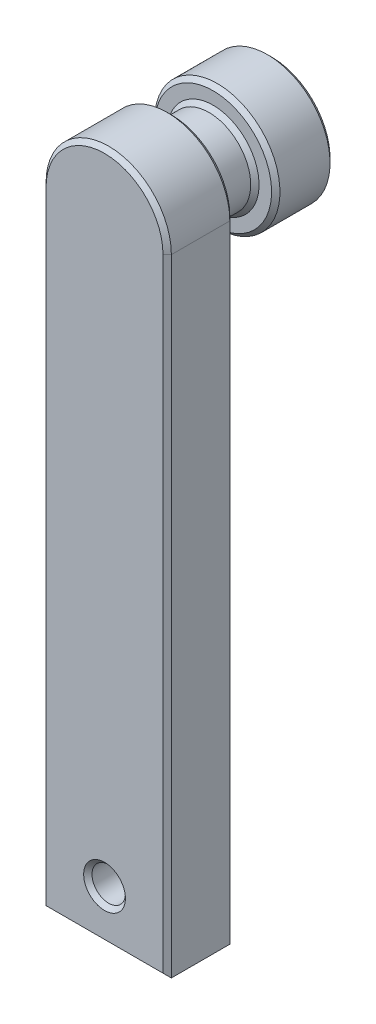
SolidWorks part; units mm, degrees
material "ABS"
ref_plane "Front Plane" through (0, 0, 0) normal (0, 0, 1) x (1, 0, 0)
ref_plane "Top Plane" through (0, 0, 0) normal (0, 1, 0) x (1, 0, 0)
ref_plane "Right Plane" through (0, 0, 0) normal (1, 0, 0) x (0, 0, -1)
sketch "Sketch3" plane through (0, 0, 0) normal (0, 0, 1) x (1, 0, 0)
  line L2 (7.5, 75) -> (7.5, 0)
  line L3 (7.5, 0) -> (-7.5, 0)
  line L4 (-7.5, 75) -> (-7.5, 0)
  line L5 (7.5, 75) -> (-7.5, 0) construction
  line L6 (7.5, 0) -> (-7.5, 75) construction
  arc A0 (-7.5, 75) -> (7.5, 75) centre (0, 75) cw
  circle A1 centre (0, 6) radius 2
  point P0 (0, 37.5)
  point P5 (0, 0)
  point P10 (0, 0)
  dimension "D3" = 6
  dimension "D4" = 4
  dimension "D1" = 75
  dimension "D2" = 15
extrude "Boss-Extrude1" add sketch "Sketch3" along normal blind 8
sketch "Sketch4" plane through (0, 0, 0) normal (0, 0, 1) x (1, 0, 0)
  circle A0 centre (0, 75) radius 5
  arc A1 (7.5, 75) -> (-7.5, 75) centre (0, 75) ccw construction
  dimension "D1" = 10
extrude "Boss-Extrude2" add sketch "Sketch4" against normal blind 5
sketch "Sketch5" plane through (0, 0, -5) normal (0, 0, -1) x (-1, 0, 0)
  circle A0 centre (0, 75) radius 7.5
  circle A1 centre (0, 75) radius 5 construction
  arc A2 (7.5, 75) -> (-7.5, 75) centre (0, 75) ccw construction
  point P2 (0, 0)
extrude "Boss-Extrude3" add sketch "Sketch5" along normal blind 7
chamfer "Chamfer1" distance 0.5 angle 45 13 edges at (0, 82.5, 8) (7.5, 37.5, 8) (0, 0, 8) (-7.5, 37.5, 8) (-7.5, 75, -5) (-7.5, 75, -12) (5, 75, -5) (-5, 75, 0) (0, 0, 0) (7.5, 37.5, 0) (-7.5, 37.5, 0) (0, 82.5, 0) (2, 6, 8)
